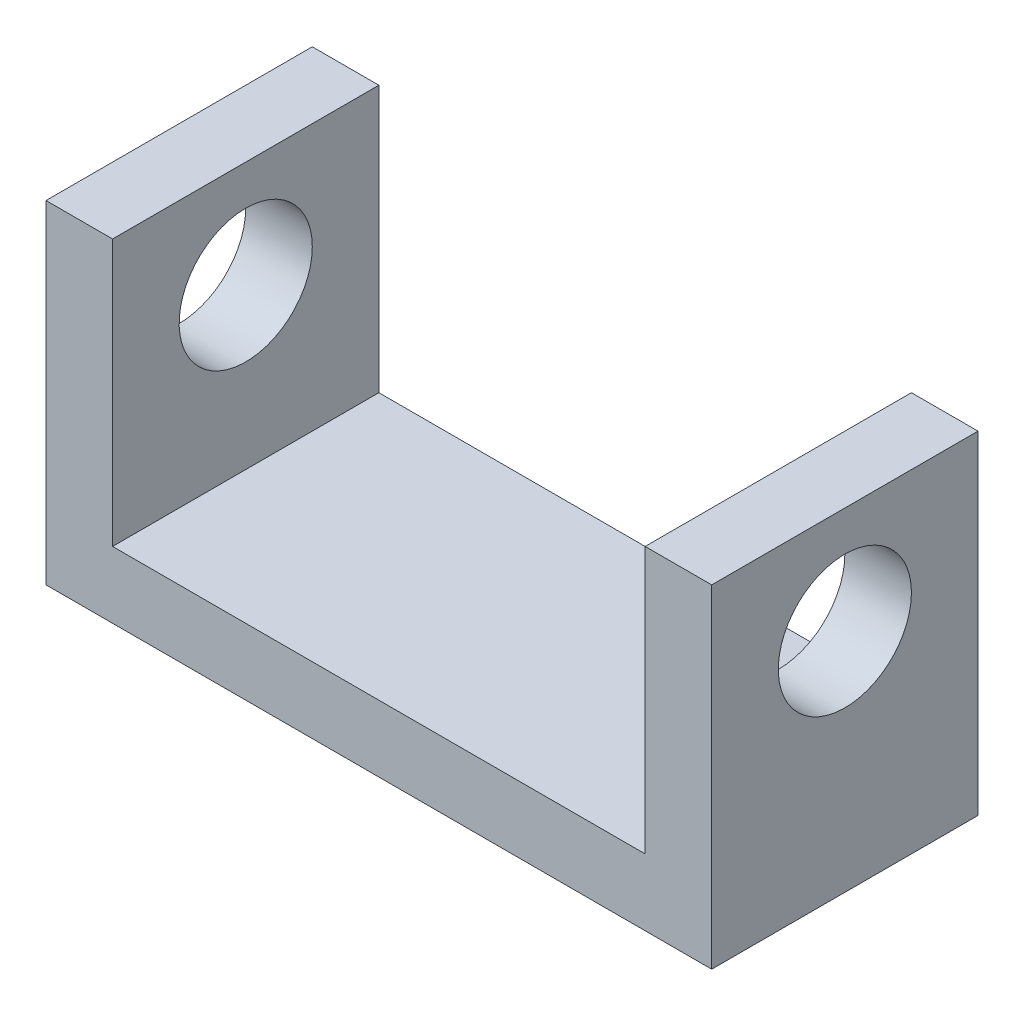
SolidWorks part; units mm, degrees
ref_plane "Front Plane" through (0, 0, 0) normal (0, 0, 1) x (1, 0, 0)
ref_plane "Top Plane" through (0, 0, 0) normal (0, 1, 0) x (1, 0, 0)
ref_plane "Right Plane" through (0, 0, 0) normal (1, 0, 0) x (0, 0, -1)
sketch "Sketch1" plane through (0, 0, 0) normal (0, 0, 1) x (1, 0, 0)
  line L0 (0, 12.7) -> (0, 0)
  line L1 (0, 0) -> (25.4, 0)
  line L2 (25.4, 0) -> (25.4, 12.7)
  dimension "D1" = 25.4
  dimension "D2" = 12.7
  dimension "D3" = 12.7
extrude "Extrude-Thin1" add sketch "Sketch1" along normal blind 12.7 thin
sketch "Sketch2" plane through (28.575, 0, 0) normal (1, 0, 0) x (0, 0, -1)
  line L0 (-6.35, 12.7) -> (-6.35, 7.62) construction
  line L1 (-12.7, 12.7) -> (0, 12.7) construction
  circle A0 centre (-6.35, 7.62) radius 3.175
  dimension "D1" = 6.35
  dimension "D2" = 5.08
extrude "Cut-Extrude1" cut sketch "Sketch2" against normal through all
